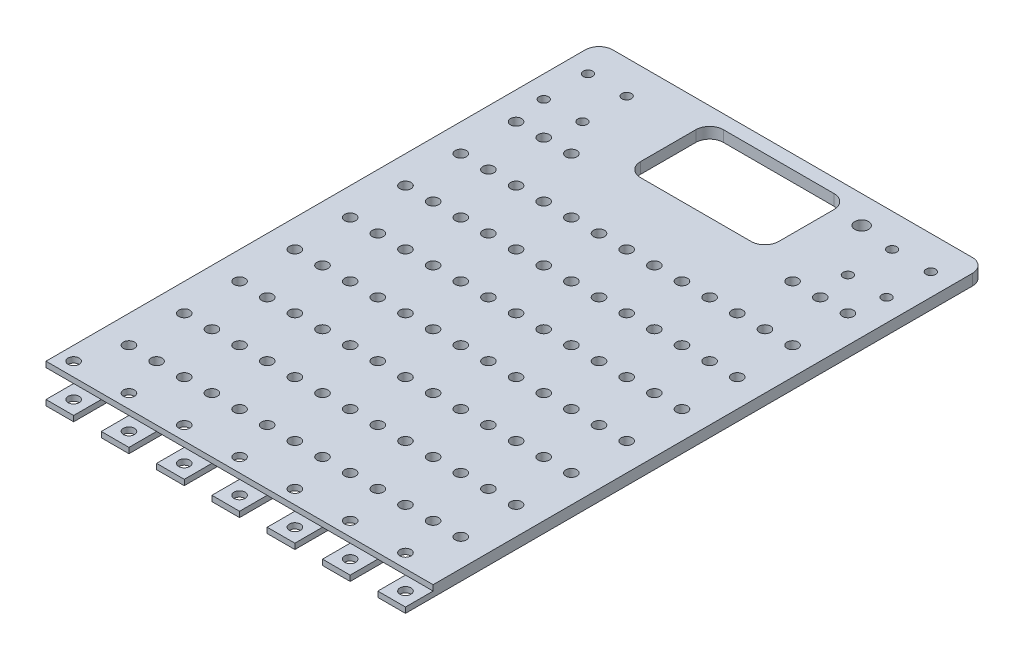
SolidWorks part; units mm, degrees
ref_plane "前视基准面" through (0, 0, 0) normal (0, 0, 1) x (1, 0, 0)
ref_plane "上视基准面" through (0, 0, 0) normal (0, 1, 0) x (1, 0, 0)
ref_plane "右视基准面" through (0, 0, 0) normal (1, 0, 0) x (0, 0, -1)
other "Configuration Table"
sketch "草图1" plane through (0, 0, 0) normal (0, 1, 0) x (1, 0, 0)
  line L0 (0, 200) -> (0, -49800) construction
  line L5 (-100, -200) -> (100, 200) construction
  line L6 (-100, 200) -> (100, -200) construction
  line L7 (-100, 200) -> (-70, 200)
  line L11 (-65, 0) -> (49935, 0) construction
  line L12 (-70, 195) -> (-70, 167)
  line L13 (70, 195) -> (70, 160)
  line L14 (-70, 167) -> (-70, 160)
  line L15 (-70, 193) -> (-40, 193)
  line L16 (-40, 193) -> (-40, 167)
  line L17 (-40, 167) -> (-70, 167)
  line L18 (-25, 190) -> (-25, 170)
  line L19 (-70, 167) -> (-70, 172)
  line L20 (-40, 167) -> (-48, 167)
  line L21 (-48, 167) -> (-48, 172)
  line L22 (-48, 172) -> (-40, 172)
  line L23 (-70, 172) -> (-62, 172)
  line L24 (-62, 172) -> (-62, 167)
  line L25 (-70, 180) -> (-40, 180) construction
  line L26 (0, 200) -> (0, 0)
  line L27 (-70, 0) -> (70, 0)
  line L28 (-70, 160) -> (0, 160)
  line L29 (100, 160) -> (70, 160)
  line L30 (-5, 195) -> (20, 195)
  line L31 (20, 165) -> (-5, 165)
  line L32 (70, -195) -> (70, -160)
  line L33 (-70, -160) -> (-70, -195)
  line L34 (-100, -160) -> (-70, -160)
  line L35 (0, 200) -> (0, 180)
  line L36 (0, 180) -> (-25, 180)
  line L39 (-20, 165) -> (-5, 165)
  line L40 (-20, 195) -> (-5, 195)
  line L41 (-5, 195) -> (-5, 165)
  line L42 (5, 195) -> (5, 165)
  line L43 (25, 180) -> (25, 170)
  line L46 (25, 180) -> (25, 190)
  line L47 (20, -165) -> (5, -165)
  line L49 (25, -180) -> (25, -190)
  line L51 (5, -195) -> (5, -165)
  line L52 (-25, -180) -> (-25, -190)
  line L54 (-20, -165) -> (-5, -165)
  line L55 (-5, -195) -> (-5, -165)
  line L57 (-120, 0) -> (-110, 0)
  line L58 (0, 200) -> (0, 180)
  line L59 (0, 200) -> (0, 190)
  line L60 (-70, 160) -> (-70, -160)
  line L61 (-65, 200) -> (65, 200)
  line L62 (70, 160) -> (70, -160)
  line L63 (-5, -195) -> (5, -195)
  line L64 (-5, -165) -> (5, -165)
  line L65 (-5, 195) -> (5, 195)
  line L66 (-5, 165) -> (5, 165)
  line L67 (-65, -200) -> (65, -200)
  line L69 (25, -165) -> (-25, -165)
  line L70 (25, -170) -> (25, -195)
  line L71 (20, -195) -> (-20, -195)
  line L72 (-25, -170) -> (-25, -195)
  circle A0 centre (-62, 172) radius 1.7
  circle A1 centre (-48, 172) radius 1.7
  circle A2 centre (-48, 188) radius 1.7
  circle A3 centre (-62, 188) radius 1.7
  circle A4 centre (48, 188) radius 1.7
  circle A5 centre (48, 172) radius 1.7
  circle A6 centre (62, 172) radius 1.7
  circle A7 centre (62, 188) radius 1.7
  circle A8 centre (62, -188) radius 1.7
  circle A9 centre (62, -172) radius 1.7
  circle A10 centre (48, -172) radius 1.7
  circle A11 centre (48, -188) radius 1.7
  circle A12 centre (-48, -172) radius 1.7
  circle A13 centre (-62, -172) radius 1.7
  circle A14 centre (-48, -188) radius 1.7
  circle A15 centre (-62, -188) radius 1.7
  circle A16 centre (-110, 0) radius 2.5
  circle A17 centre (-110, 50) radius 2.5
  circle A18 centre (-110, -50) radius 2.5
  circle A19 centre (110, -50) radius 2.5
  circle A20 centre (110, 0) radius 2.5
  circle A21 centre (110, 50) radius 2.5
  circle A22 centre (0, 190) radius 2.5
  circle A23 centre (35, 190) radius 2.5
  circle A26 centre (-50, 20) radius 2
  circle A27 centre (-50, 40) radius 2
  circle A28 centre (-50, 60) radius 2
  circle A29 centre (-50, 80) radius 2
  circle A30 centre (-50, 100) radius 2
  circle A31 centre (-50, 120) radius 2
  circle A32 centre (-50, 140) radius 2
  circle A33 centre (-50, 160) radius 2
  circle A34 centre (-60, 20) radius 2
  circle A35 centre (-60, 40) radius 2
  circle A36 centre (-60, 60) radius 2
  circle A37 centre (-60, 80) radius 2
  circle A38 centre (-60, 100) radius 2
  circle A39 centre (-60, 120) radius 2
  circle A40 centre (-60, 140) radius 2
  circle A41 centre (-60, 160) radius 2
  circle A43 centre (-40, 160) radius 2
  circle A44 centre (-40, 140) radius 2
  circle A45 centre (-40, 120) radius 2
  circle A46 centre (-40, 100) radius 2
  circle A47 centre (-40, 80) radius 2
  circle A48 centre (-40, 60) radius 2
  circle A49 centre (-40, 40) radius 2
  circle A50 centre (-40, 20) radius 2
  circle A52 centre (-30, 140) radius 2
  circle A53 centre (-30, 120) radius 2
  circle A54 centre (-30, 100) radius 2
  circle A55 centre (-30, 80) radius 2
  circle A56 centre (-30, 60) radius 2
  circle A57 centre (-30, 40) radius 2
  circle A58 centre (-30, 20) radius 2
  circle A60 centre (-20, 140) radius 2
  circle A61 centre (-20, 120) radius 2
  circle A62 centre (-20, 100) radius 2
  circle A63 centre (-20, 80) radius 2
  circle A64 centre (-20, 60) radius 2
  circle A65 centre (-20, 40) radius 2
  circle A66 centre (-20, 20) radius 2
  circle A68 centre (-10, 140) radius 2
  circle A69 centre (-10, 120) radius 2
  circle A70 centre (-10, 100) radius 2
  circle A71 centre (-10, 80) radius 2
  circle A72 centre (-10, 60) radius 2
  circle A73 centre (-10, 40) radius 2
  circle A74 centre (-10, 20) radius 2
  circle A76 centre (0, 140) radius 2
  circle A77 centre (0, 120) radius 2
  circle A78 centre (0, 100) radius 2
  circle A79 centre (0, 80) radius 2
  circle A80 centre (0, 60) radius 2
  circle A81 centre (0, 40) radius 2
  circle A82 centre (0, 20) radius 2
  circle A84 centre (10, 140) radius 2
  circle A85 centre (10, 120) radius 2
  circle A86 centre (10, 100) radius 2
  circle A87 centre (10, 80) radius 2
  circle A88 centre (10, 60) radius 2
  circle A89 centre (10, 40) radius 2
  circle A90 centre (10, 20) radius 2
  circle A92 centre (20, 140) radius 2
  circle A93 centre (20, 120) radius 2
  circle A94 centre (20, 100) radius 2
  circle A95 centre (20, 80) radius 2
  circle A96 centre (20, 60) radius 2
  circle A97 centre (20, 40) radius 2
  circle A98 centre (20, 20) radius 2
  circle A100 centre (30, 140) radius 2
  circle A101 centre (30, 120) radius 2
  circle A102 centre (30, 100) radius 2
  circle A103 centre (30, 80) radius 2
  circle A104 centre (30, 60) radius 2
  circle A105 centre (30, 40) radius 2
  circle A106 centre (30, 20) radius 2
  circle A107 centre (40, 160) radius 2
  circle A108 centre (40, 140) radius 2
  circle A109 centre (40, 120) radius 2
  circle A110 centre (40, 100) radius 2
  circle A111 centre (40, 80) radius 2
  circle A112 centre (40, 60) radius 2
  circle A113 centre (40, 40) radius 2
  circle A114 centre (40, 20) radius 2
  circle A115 centre (50, 160) radius 2
  circle A116 centre (50, 140) radius 2
  circle A117 centre (50, 120) radius 2
  circle A118 centre (50, 100) radius 2
  circle A119 centre (50, 80) radius 2
  circle A120 centre (50, 60) radius 2
  circle A121 centre (50, 40) radius 2
  circle A122 centre (50, 20) radius 2
  circle A123 centre (60, 160) radius 2
  circle A124 centre (60, 140) radius 2
  circle A125 centre (60, 120) radius 2
  circle A126 centre (60, 100) radius 2
  circle A127 centre (60, 80) radius 2
  circle A128 centre (60, 60) radius 2
  circle A129 centre (60, 40) radius 2
  circle A130 centre (60, 20) radius 2
  circle A131 centre (60, -20) radius 2
  circle A132 centre (60, -40) radius 2
  circle A133 centre (60, -60) radius 2
  circle A134 centre (60, -80) radius 2
  circle A135 centre (60, -100) radius 2
  circle A136 centre (60, -120) radius 2
  circle A137 centre (60, -140) radius 2
  circle A138 centre (60, -160) radius 2
  circle A139 centre (50, -20) radius 2
  circle A140 centre (50, -40) radius 2
  circle A141 centre (50, -60) radius 2
  circle A142 centre (50, -80) radius 2
  circle A143 centre (50, -100) radius 2
  circle A144 centre (50, -120) radius 2
  circle A145 centre (50, -140) radius 2
  circle A146 centre (50, -160) radius 2
  circle A147 centre (40, -20) radius 2
  circle A148 centre (40, -40) radius 2
  circle A149 centre (40, -60) radius 2
  circle A150 centre (40, -80) radius 2
  circle A151 centre (40, -100) radius 2
  circle A152 centre (40, -120) radius 2
  circle A153 centre (40, -140) radius 2
  circle A154 centre (40, -160) radius 2
  circle A155 centre (30, -20) radius 2
  circle A156 centre (30, -40) radius 2
  circle A157 centre (30, -60) radius 2
  circle A158 centre (30, -80) radius 2
  circle A159 centre (30, -100) radius 2
  circle A160 centre (30, -120) radius 2
  circle A161 centre (30, -140) radius 2
  circle A163 centre (20, -20) radius 2
  circle A164 centre (20, -40) radius 2
  circle A165 centre (20, -60) radius 2
  circle A166 centre (20, -80) radius 2
  circle A167 centre (20, -100) radius 2
  circle A168 centre (20, -120) radius 2
  circle A169 centre (20, -140) radius 2
  circle A171 centre (10, -20) radius 2
  circle A172 centre (10, -40) radius 2
  circle A173 centre (10, -60) radius 2
  circle A174 centre (10, -80) radius 2
  circle A175 centre (10, -100) radius 2
  circle A176 centre (10, -120) radius 2
  circle A177 centre (10, -140) radius 2
  circle A179 centre (0, -20) radius 2
  circle A180 centre (0, -40) radius 2
  circle A181 centre (0, -60) radius 2
  circle A182 centre (0, -80) radius 2
  circle A183 centre (0, -100) radius 2
  circle A184 centre (0, -120) radius 2
  circle A185 centre (0, -140) radius 2
  circle A187 centre (-10, -20) radius 2
  circle A188 centre (-10, -40) radius 2
  circle A189 centre (-10, -60) radius 2
  circle A190 centre (-10, -80) radius 2
  circle A191 centre (-10, -100) radius 2
  circle A192 centre (-10, -120) radius 2
  circle A193 centre (-10, -140) radius 2
  circle A195 centre (-20, -20) radius 2
  circle A196 centre (-20, -40) radius 2
  circle A197 centre (-20, -60) radius 2
  circle A198 centre (-20, -80) radius 2
  circle A199 centre (-20, -100) radius 2
  circle A200 centre (-20, -120) radius 2
  circle A201 centre (-20, -140) radius 2
  circle A203 centre (-30, -20) radius 2
  circle A204 centre (-30, -40) radius 2
  circle A205 centre (-30, -60) radius 2
  circle A206 centre (-30, -80) radius 2
  circle A207 centre (-30, -100) radius 2
  circle A208 centre (-30, -120) radius 2
  circle A209 centre (-30, -140) radius 2
  circle A211 centre (-40, -20) radius 2
  circle A212 centre (-40, -40) radius 2
  circle A213 centre (-40, -60) radius 2
  circle A214 centre (-40, -80) radius 2
  circle A215 centre (-40, -100) radius 2
  circle A216 centre (-40, -120) radius 2
  circle A217 centre (-40, -140) radius 2
  circle A218 centre (-40, -160) radius 2
  circle A219 centre (-60, -160) radius 2
  circle A220 centre (-60, -140) radius 2
  circle A221 centre (-60, -120) radius 2
  circle A222 centre (-60, -100) radius 2
  circle A223 centre (-60, -80) radius 2
  circle A224 centre (-60, -60) radius 2
  circle A225 centre (-60, -40) radius 2
  circle A226 centre (-60, -20) radius 2
  circle A227 centre (-50, -160) radius 2
  circle A228 centre (-50, -140) radius 2
  circle A229 centre (-50, -120) radius 2
  circle A230 centre (-50, -100) radius 2
  circle A231 centre (-50, -80) radius 2
  circle A232 centre (-50, -60) radius 2
  circle A233 centre (-50, -40) radius 2
  circle A234 centre (-50, -20) radius 2
  arc A235 (70, -195) -> (65, -200) centre (65, -195) cw
  arc A236 (20, -195) -> (25, -190) centre (20, -190) ccw
  arc A237 (25, -170) -> (20, -165) centre (20, -170) ccw
  arc A238 (-20, -165) -> (-25, -170) centre (-20, -170) ccw
  arc A239 (-25, -190) -> (-20, -195) centre (-20, -190) ccw
  arc A240 (-65, -200) -> (-70, -195) centre (-65, -195) cw
  arc A241 (-20, 195) -> (-25, 190) centre (-20, 190) ccw
  arc A242 (-25, 170) -> (-20, 165) centre (-20, 170) ccw
  arc A243 (20, 165) -> (25, 170) centre (20, 170) ccw
  arc A244 (25, 190) -> (20, 195) centre (20, 190) ccw
  arc A245 (70, 195) -> (65, 200) centre (65, 195) ccw
  arc A246 (-70, 195) -> (-65, 200) centre (-65, 195) cw
  circle A247 centre (-30, 160) radius 2 [skipped]
  circle A248 centre (-20, 160) radius 2 [skipped]
  circle A249 centre (-10, 160) radius 2 [skipped]
  circle A250 centre (0, 160) radius 2 [skipped]
  circle A251 centre (10, 160) radius 2 [skipped]
  circle A252 centre (20, 160) radius 2 [skipped]
  circle A253 centre (30, 160) radius 2 [skipped]
  point P0 (0, 0)
  point P541 (-25, 195)
  point P544 (-25, 165)
  point P547 (25, 165)
  point P550 (25, 195)
  point P553 (70, 200)
  dimension "D12" = 3.4
  dimension "D13" = 3.4
  dimension "D19" = 5
  dimension "D23" = 5
  dimension "D26" = 12
  dimension "D8" = 5
  dimension "D1" = 200
  dimension "D2" = 400
  dimension "D3" = 140
  dimension "D4" = 40
  dimension "D5" = 7
  dimension "D6" = 7
  dimension "D7" = 30
  dimension "D9" = 5
  dimension "D10" = 8
  dimension "D11" = 8
  dimension "D14" = 25
  dimension "D16" = 15
  dimension "D18" = 10
  dimension "D21" = 20
  dimension "D22" = 10
  dimension "D20" = 2
  dimension "D24" = 2
extrude "凸台-拉伸1" add sketch "草图1" along normal blind 4
sketch "草图2" plane through (0, 4, 0) normal (0, 1, 0) x (1, 0, 0)
  line L0 (-70, 0) -> (70, 0)
  line L1 (-70, 195) -> (-70, -195) construction
  line L2 (70, 195) -> (70, -195) construction
  line L3 (-70, 0) -> (-70, 10)
  line L4 (-70, 10) -> (-60, 10)
  line L5 (-60, 10) -> (-60, 0)
  line L6 (-60, 10) -> (-52.8871, 10)
  line L7 (-60, 0) -> (-50, 0)
  line L8 (-50, 0) -> (-50, 10)
  line L9 (-50, 10) -> (-40, 10)
  line L10 (-40, 10) -> (-40, 0)
  line L11 (-30, 10) -> (-20, 10)
  line L12 (-30, 0) -> (-30, 10)
  line L13 (-20, 10) -> (-20, 0)
  line L14 (-10, 10) -> (0, 10)
  line L15 (-10, 0) -> (-10, 10)
  line L16 (0, 10) -> (0, 0)
  line L17 (10, 10) -> (20, 10)
  line L18 (10, 0) -> (10, 10)
  line L19 (20, 10) -> (20, 0)
  line L20 (30, 10) -> (40, 10)
  line L21 (30, 0) -> (30, 10)
  line L22 (40, 10) -> (40, 0)
  line L23 (50, 10) -> (60, 10)
  line L24 (50, 0) -> (50, 10)
  line L25 (60, 10) -> (60, 0)
  line L26 (-70, 10) -> (-60, 0) construction
  line L27 (-60, 10) -> (-70, 0) construction
  line L28 (-40, -10) -> (-30, -10)
  line L29 (-60, 0) -> (-50, 0)
  line L30 (-60, 0) -> (-60, -10)
  line L31 (-60, -10) -> (-50, -10)
  line L32 (-50, 0) -> (-50, -10)
  line L33 (-30, 0) -> (-30, -10)
  line L34 (-40, 0) -> (-40, -10)
  line L35 (-20, -10) -> (-10, -10)
  line L36 (-10, 0) -> (-10, -10)
  line L37 (-20, 0) -> (-20, -10)
  line L38 (0, -10) -> (10, -10)
  line L39 (10, 0) -> (10, -10)
  line L40 (0, 0) -> (0, -10)
  line L41 (20, -10) -> (30, -10)
  line L42 (30, 0) -> (30, -10)
  line L43 (20, 0) -> (20, -10)
  line L44 (40, -10) -> (50, -10)
  line L45 (50, 0) -> (50, -10)
  line L46 (40, 0) -> (40, -10)
  line L47 (60, -10) -> (70, -10)
  line L48 (70, 0) -> (70, -10)
  line L49 (60, 0) -> (60, -10)
  line L50 (-60, 0) -> (-50, -10) construction
  line L51 (-50, 0) -> (-60, -10) construction
  line L52 (-70, 0) -> (-70, -200)
  line L53 (-70, -200) -> (70, -200)
  line L54 (70, -200) -> (70, 0)
  line L55 (-60, 0) -> (-60, -10)
  circle A0 centre (-65, 5) radius 2
  circle A1 centre (-45, 5) radius 2
  circle A2 centre (-25, 5) radius 2
  circle A3 centre (-5, 5) radius 2
  circle A4 centre (15, 5) radius 2
  circle A5 centre (35, 5) radius 2
  circle A6 centre (55, 5) radius 2
  circle A7 centre (-55, -5) radius 2
  circle A8 centre (-35, -5) radius 2
  circle A9 centre (-15, -5) radius 2
  circle A10 centre (5, -5) radius 2
  circle A11 centre (25, -5) radius 2
  circle A12 centre (45, -5) radius 2
  circle A13 centre (65, -5) radius 2
  dimension "D7" = 4
  dimension "D12" = 4
  dimension "D1" = 10
  dimension "D2" = 10
  dimension "D3" = 10
  dimension "D4" = 10
  dimension "D5" = 10
  dimension "D6" = 6
  dimension "D9" = 10
  dimension "D10" = 10
  dimension "D8" = 7
  dimension "D11" = 7
  dimension "D13" = 7
extrude "切除-拉伸3" cut sketch "草图2" against normal blind 4 contours A0 | A7 | A1 | A8 | A2 | A9 | A10 | A4 | A5 | A6 | A3 | A11 | A12 | A13
sketch "草图3" plane through (0, 4, 0) normal (0, 1, 0) x (1, 0, 0)
  line L1 (-60, -10) -> (-50, -10)
  line L2 (-60, -10) -> (-60, 0)
  line L3 (-60, 0) -> (-50, 0)
  line L4 (-50, -10) -> (-50, 0)
  line L5 (-40, -10) -> (-30, -10)
  line L6 (-40, -10) -> (-40, 0)
  line L7 (-40, 0) -> (-30, 0)
  line L8 (-30, -10) -> (-30, 0)
  line L9 (-20, -10) -> (-10, -10)
  line L10 (-20, -10) -> (-20, 0)
  line L11 (-20, 0) -> (-10, 0)
  line L12 (-10, -10) -> (-10, 0)
  line L13 (0, -10) -> (10, -10)
  line L14 (0, -10) -> (0, 0)
  line L15 (0, 0) -> (10, 0)
  line L16 (10, -10) -> (10, 0)
  line L17 (20, -10) -> (30, -10)
  line L18 (20, -10) -> (20, 0)
  line L19 (20, 0) -> (30, 0)
  line L20 (30, -10) -> (30, 0)
  line L21 (40, -10) -> (50, -10)
  line L22 (40, -10) -> (40, 0)
  line L23 (40, 0) -> (50, 0)
  line L24 (50, -10) -> (50, 0)
  line L25 (60, -10) -> (70, -10)
  line L26 (60, -10) -> (60, 0)
  line L27 (60, 0) -> (70, 0)
  line L28 (70, -10) -> (70, 0)
extrude "切除-拉伸4" cut sketch "草图3" against normal blind 2
sketch "草图5" plane through (0, 0, 0) normal (0, -1, 0) x (1, 0, 0)
  line L1 (-70, 0) -> (-60, 0)
  line L2 (-70, 0) -> (-70, -10)
  line L3 (-70, -10) -> (-60, -10)
  line L4 (-60, 0) -> (-60, -10)
  line L5 (-50, 0) -> (-40, 0)
  line L6 (-50, 0) -> (-50, -10)
  line L7 (-50, -10) -> (-40, -10)
  line L8 (-40, 0) -> (-40, -10)
  line L9 (-30, 0) -> (-20, 0)
  line L10 (-30, 0) -> (-30, -10)
  line L11 (-30, -10) -> (-20, -10)
  line L12 (-20, 0) -> (-20, -10)
  line L13 (-10, 0) -> (0, 0)
  line L14 (-10, 0) -> (-10, -10)
  line L15 (-10, -10) -> (0, -10)
  line L16 (0, 0) -> (0, -10)
  line L17 (10, 0) -> (20, 0)
  line L18 (10, 0) -> (10, -10)
  line L19 (10, -10) -> (20, -10)
  line L20 (20, 0) -> (20, -10)
  line L21 (30, 0) -> (40, 0)
  line L22 (30, 0) -> (30, -10)
  line L23 (30, -10) -> (40, -10)
  line L24 (40, 0) -> (40, -10)
  line L25 (50, 0) -> (60, 0)
  line L26 (50, 0) -> (50, -10)
  line L27 (50, -10) -> (60, -10)
  line L28 (60, 0) -> (60, -10)
extrude "切除-拉伸7" cut sketch "草图5" against normal blind 1.98
sketch "草图6" plane through (0, 4, 0) normal (0, 1, 0) x (1, 0, 0)
  line L0 (-70, 0) -> (-60, 0)
  line L1 (-60, 0) -> (-60, -10)
  line L2 (-60, -10) -> (-50, -10)
  line L3 (-50, -10) -> (-50, 0)
  line L4 (-50, 0) -> (-40, 0)
  line L5 (-40, 0) -> (-40, -10)
  line L6 (-40, -10) -> (-30, -10)
  line L7 (-30, -10) -> (-30, 0)
  line L8 (-30, 0) -> (-20, 0)
  line L9 (-20, 0) -> (-20, -10)
  line L10 (-20, -10) -> (-10, -10)
  line L11 (-10, -10) -> (-10, 0)
  line L12 (-10, 0) -> (0, 0)
  line L13 (0, 0) -> (0, -10)
  line L14 (0, -10) -> (10, -10)
  line L15 (10, -10) -> (10, 0)
  line L16 (10, 0) -> (20, 0)
  line L17 (20, 0) -> (20, -10)
  line L18 (20, -10) -> (30, -10)
  line L19 (30, -10) -> (30, 0)
  line L20 (30, 0) -> (40, 0)
  line L21 (40, 0) -> (40, -10)
  line L22 (40, -10) -> (50, -10)
  line L23 (50, -10) -> (50, 0)
  line L24 (50, 0) -> (60, 0)
  line L25 (60, 0) -> (60, -10)
  line L26 (60, -10) -> (70, -10)
  line L27 (70, -10) -> (70, -200)
  line L28 (70, -200) -> (-70, -200)
  line L29 (-70, -200) -> (-70, 0)
extrude "切除-拉伸8" cut sketch "草图6" against normal blind 4
